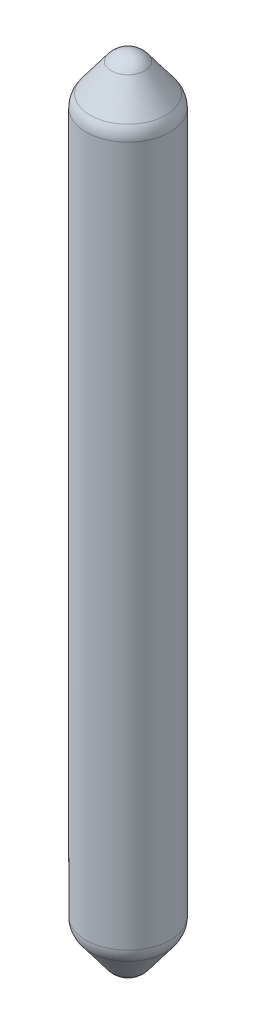
SolidWorks part; units mm, degrees
ref_plane "Front Plane" through (0, 0, 0) normal (1, 0, 0) x (0, 1, 0)
ref_plane "Top Plane" through (0, 0, 0) normal (0, 0, 1) x (0, 1, 0)
ref_plane "Right Plane" through (0, 0, 0) normal (0, 1, 0) x (-1, 0, 0)
sketch "Sketch1" plane through (0, 0, 0) normal (0, 1, 0) x (-1, 0, 0)
  circle A0 centre (0, 0) radius 20
  dimension "D1" = 40
extrude "Boss-Extrude1" add sketch "Sketch1" along normal mid plane 340
sketch "Sketch2" plane through (0, 0, 0) normal (0, 0, 1) x (0, 1, 0)
  line L0 (-170, 20) -> (-170, 0)
  line L1 (-170, 20) -> (-170, -20) construction
  line L2 (-170, 0) -> (-180, 0)
  line L3 (-170, 20) -> (-186, 8)
  line L4 (-180, 0) -> (-190, 0)
  line L5 (-190, 0) -> (233.4882, 0) construction
  arc A0 (-186, 8) -> (-190, 0) centre (-180, 0) ccw
  dimension "D1" = 20
  dimension "D4" = 10
  dimension "D2" = 0
  dimension "D3" = 0
revolve "Revolve1" add sketch "Sketch2" angle 360 about L5
mirror "Mirror2" about plane through (0, 0, 0) normal (0, 1, 0) of "Revolve1"
fillet "Fillet1" radius 10 2 edges at (0, 170, 20) (20, -170, 0)
